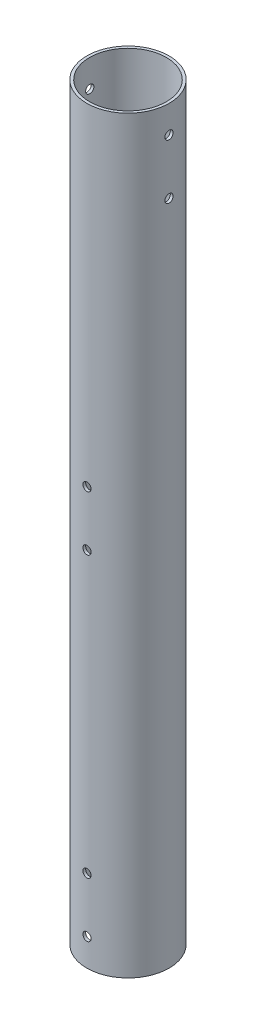
SolidWorks part; units mm, degrees
ref_plane "前基準面" through (0, 0, 0) normal (0, 0, 1) x (1, 0, 0)
ref_plane "上基準面" through (0, 0, 0) normal (0, 1, 0) x (1, 0, 0)
ref_plane "右基準面" through (0, 0, 0) normal (1, 0, 0) x (0, 0, -1)
sketch "草圖1" plane through (0, 0, 0) normal (0, 1, 0) x (1, 0, 0)
  circle A0 centre (0, 0) radius 15
  dimension "D1" = 30
extrude "填料-伸長1" add sketch "草圖1" along normal blind 273
sketch "草圖2" plane through (0, 0, 0) normal (0, 0, 1) x (1, 0, 0)
  circle A0 centre (0, 10) radius 1.5
  circle A1 centre (0, 30) radius 1.5
  circle A2 centre (0, 132) radius 1.5
  circle A3 centre (0, 152) radius 1.5
  dimension "D1" = 3
  dimension "D2" = 20
  dimension "D3" = 10
  dimension "D4" = 20
  dimension "D5" = 102
extrude "除料-伸長1" cut sketch "草圖2" against normal through all both and the other way through all
sketch "草圖3" plane through (0, 0, 0) normal (1, 0, 0) x (0, 0, -1)
  line L0 (15, 273) -> (-15, 273) construction
  circle A0 centre (0, 263) radius 1.5
  circle A1 centre (0, 243) radius 1.5
  dimension "D1" = 3
  dimension "D2" = 10
  dimension "D3" = 20
extrude "除料-伸長2" cut sketch "草圖3" against normal through all both and the other way through all
sketch "草圖4" plane through (0, 273, 0) normal (0, 1, 0) x (1, 0, 0)
  circle A2 centre (0, 0) radius 14
  circle A3 centre (0, 0) radius 14
  dimension "D1" = 1
extrude "除料-伸長3" cut sketch "草圖4" against normal up to next
